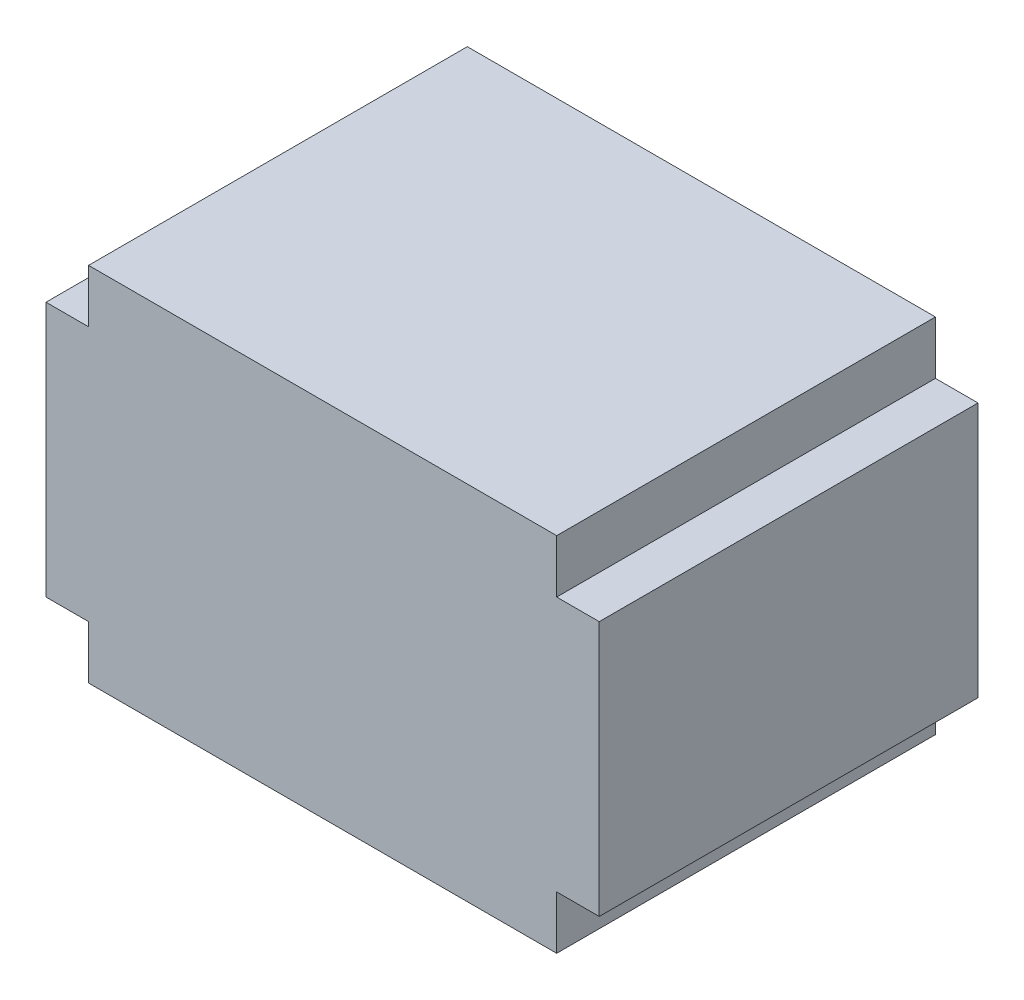
SolidWorks part; units mm, degrees
ref_plane "前视基准面" through (0, 0, 0) normal (0, 0, 1) x (1, 0, 0)
ref_plane "上视基准面" through (0, 0, 0) normal (0, 1, 0) x (1, 0, 0)
ref_plane "右视基准面" through (0, 0, 0) normal (1, 0, 0) x (0, 0, -1)
sketch "草图1" plane through (0, 0, 0) normal (0, 0, 1) x (1, 0, 0)
  line L0 (-1.1, -0.85) -> (-1.1, -0.6)
  line L1 (-1.1, -0.6) -> (-1.3, -0.6)
  line L2 (-1.3, -0.6) -> (-1.3, 0.6)
  line L3 (-1.3, 0.6) -> (-1.1, 0.6)
  line L4 (-1.1, 0.6) -> (-1.1, 0.85)
  line L5 (-1.1, 0.85) -> (1.1, 0.85)
  line L6 (1.1, 0.85) -> (1.1, 0.6)
  line L7 (1.1, 0.6) -> (1.3, 0.6)
  line L8 (1.3, 0.6) -> (1.3, -0.6)
  line L9 (1.3, -0.6) -> (1.1, -0.6)
  line L10 (1.1, -0.6) -> (1.1, -0.85)
  line L11 (1.1, -0.85) -> (-1.1, -0.85)
extrude "Component_Outline" add sketch "草图1" along normal blind 1.78 separate body
sketch3d "3D草图1"
  line L0 (0, 0, 0) -> (1, 0, 0)
  line L1 (0, 0, 0) -> (0, 1, 0)
  line L2 (0, 0, 0) -> (0, 0, 1)
  point P0 (0, 0, 0)
